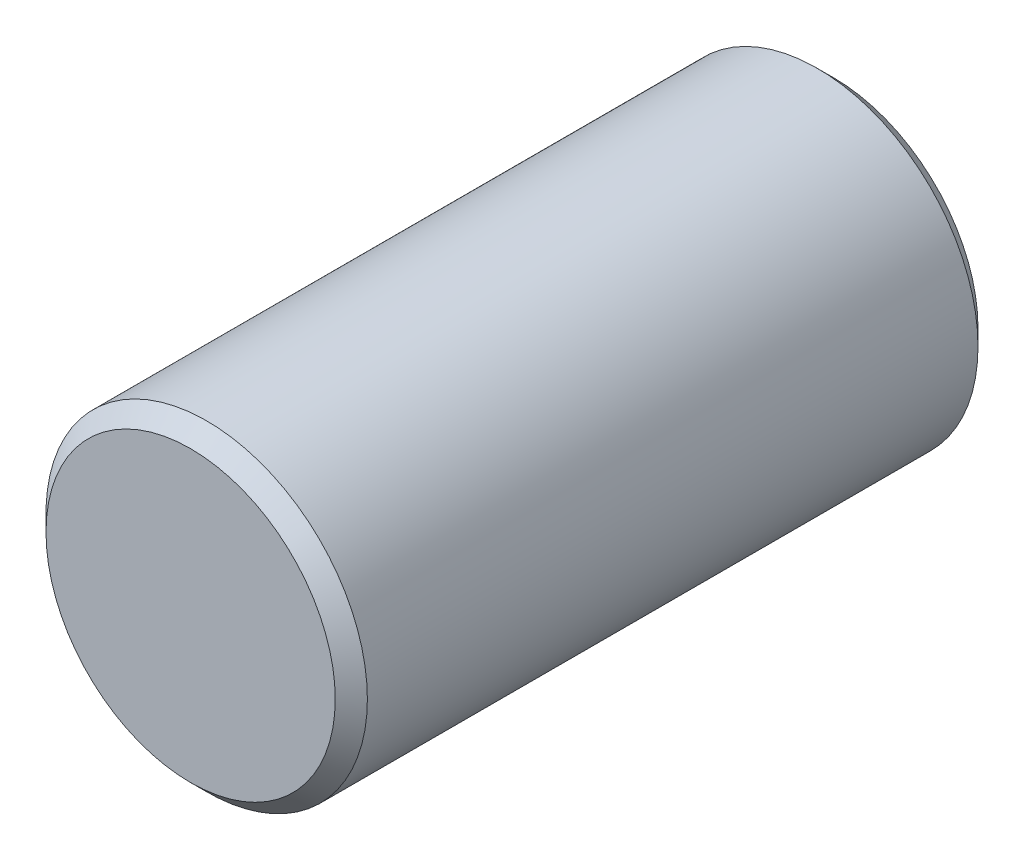
SolidWorks part; units mm, degrees
ref_plane "前视基准面" through (0, 0, 0) normal (0, 0, 1) x (1, 0, 0)
ref_plane "上视基准面" through (0, 0, 0) normal (0, 1, 0) x (1, 0, 0)
ref_plane "右视基准面" through (0, 0, 0) normal (1, 0, 0) x (0, 0, -1)
sketch "草图1" plane through (0, 0, 0) normal (0, 0, 1) x (1, 0, 0)
  circle A0 centre (0, 0) radius 2
  dimension "D1" = 4
extrude "凸台-拉伸1" add sketch "草图1" along normal mid plane 8
chamfer "倒角1" distance 0.2 angle 45 2 edges at (2, 0, -4) (2, 0, 4)
